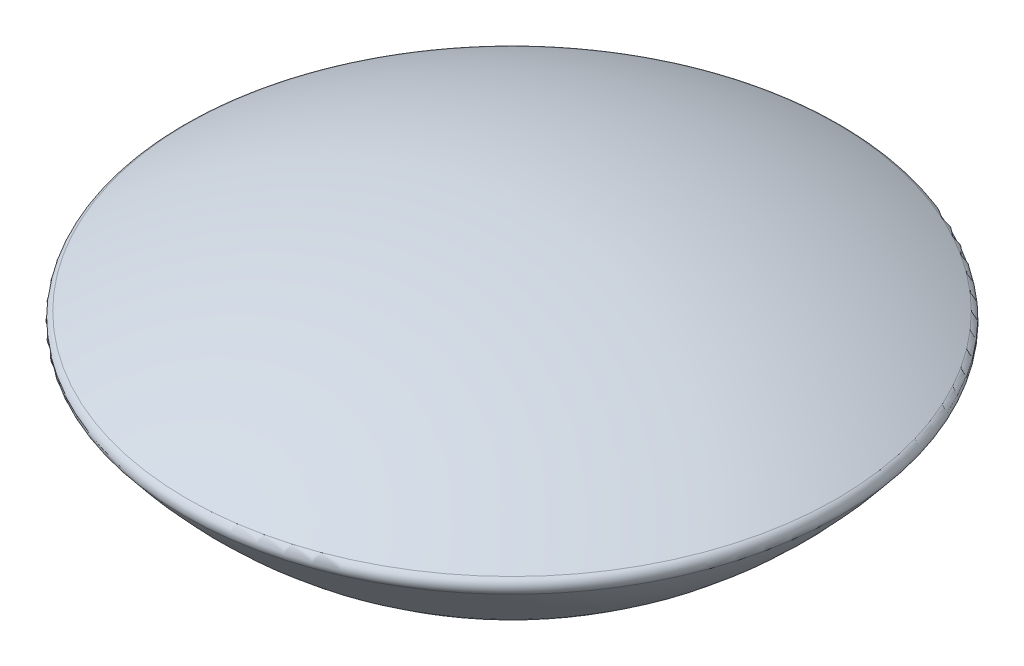
SolidWorks part; units mm, degrees
ref_plane "Front" through (0, 0, 0) normal (0, 0, 1) x (1, 0, 0)
ref_plane "Top" through (0, 0, 0) normal (0, 1, 0) x (1, 0, 0)
ref_plane "Right" through (0, 0, 0) normal (1, 0, 0) x (0, 0, -1)
sketch "Sketch6" plane through (0, 0, 0) normal (0, 0, 1) x (1, 0, 0)
  line L0 (0, 7.033) -> (0, -0.4239) construction
  line L8 (0, 4.08) -> (0, 0.38)
  line L9 (0, -16.2) -> (0, -16.52)
  line L12 (0, 4.08) -> (0, -60.6715) construction
  arc A3 (4.705, 2.904) -> (0, 4.08) centre (0, -5.92) ccw
  arc A4 (0, 0.38) -> (4.7466, 2.7099) centre (0, 6.38) ccw
  arc A10 (4.7466, 2.7099) -> (4.705, 2.904) centre (4.6439, 2.7894) ccw
  dimension "D15" = 16.58
  dimension "D17" = 10
  dimension "D18" = 6
  dimension "D11" = 3.7
revolve "lens" add sketch "Sketch6" angle 360 about L0
